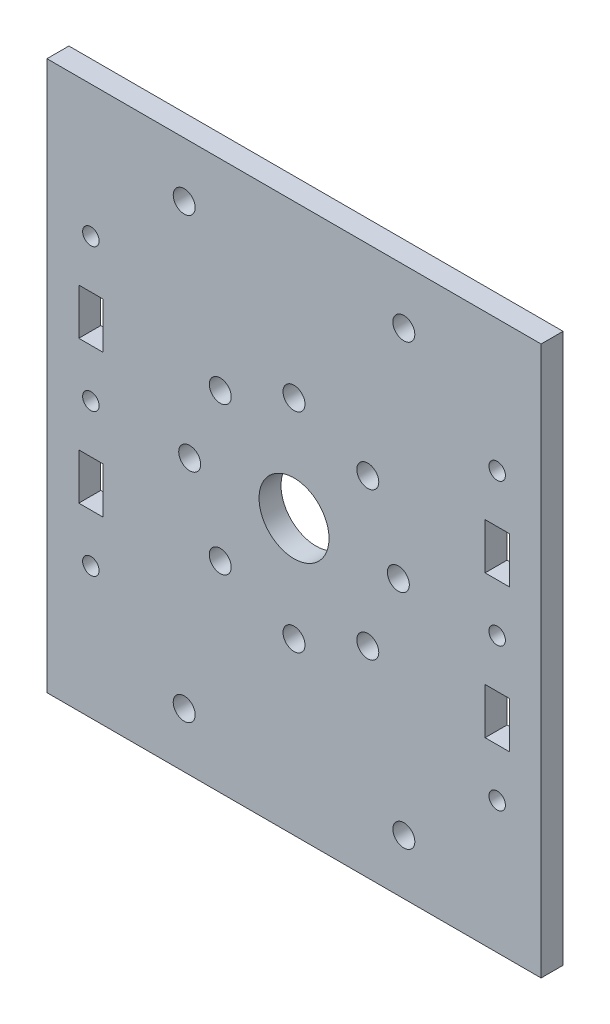
SolidWorks part; units mm, degrees
ref_plane "前视基准面" through (0, 0, 0) normal (0, 0, 1) x (1, 0, 0)
ref_plane "上视基准面" through (0, 0, 0) normal (0, 1, 0) x (1, 0, 0)
ref_plane "右视基准面" through (0, 0, 0) normal (1, 0, 0) x (0, 0, -1)
sketch "草图1" plane through (0, 0, 0) normal (0, 0, 1) x (1, 0, 0)
  line L0 (0, 0) -> (0, -40) construction
  line L1 (0, -40) -> (20, -40) construction
  line L2 (0, -40) -> (-20, -40) construction
  line L3 (0, 0) -> (19, 0) construction
  line L4 (34.8, -17.2) -> (39.2, -17.2)
  line L5 (45, -50) -> (-45, -50)
  line L6 (45, -50) -> (45, 50)
  line L7 (45, 50) -> (-45, 50)
  line L8 (-45, -50) -> (-45, 50)
  line L9 (45, -50) -> (-45, 50) construction
  line L10 (45, 50) -> (-45, -50) construction
  line L11 (34.8, 17.2) -> (39.2, 17.2)
  line L12 (34.8, 17.2) -> (34.8, 8.8)
  line L13 (34.8, 8.8) -> (39.2, 8.8)
  line L14 (39.2, 17.2) -> (39.2, 8.8)
  line L15 (34.8, 17.2) -> (39.2, 8.8) construction
  line L16 (34.8, 8.8) -> (39.2, 17.2) construction
  line L17 (34.8, -17.2) -> (34.8, -8.8)
  line L18 (39.2, -17.2) -> (39.2, -8.8)
  line L19 (34.8, -8.8) -> (39.2, -8.8)
  line L20 (0, 19) -> (0, 0) construction
  line L21 (-34.8, 17.2) -> (-39.2, 17.2)
  line L22 (-39.2, 17.2) -> (-39.2, 8.8)
  line L23 (-34.8, 17.2) -> (-34.8, 8.8)
  line L24 (-34.8, 8.8) -> (-39.2, 8.8)
  line L25 (-34.8, -8.8) -> (-39.2, -8.8)
  line L26 (-34.8, -17.2) -> (-39.2, -17.2)
  line L27 (-34.8, -17.2) -> (-34.8, -8.8)
  line L28 (-39.2, -17.2) -> (-39.2, -8.8)
  circle A0 centre (0, 0) radius 19 construction
  circle A1 centre (0, 0) radius 6.3725
  circle A2 centre (0, -19) radius 2
  circle A3 centre (-13.435, -13.435) radius 2
  circle A4 centre (-19, 0) radius 2
  circle A5 centre (-13.435, 13.435) radius 2
  circle A6 centre (0, 19) radius 2
  circle A7 centre (13.435, 13.435) radius 2
  circle A8 centre (19, 0) radius 2
  circle A9 centre (13.435, -13.435) radius 2
  circle A10 centre (-20, -40) radius 2
  circle A11 centre (20, -40) radius 2
  circle A12 centre (20, 40) radius 2
  circle A13 centre (-20, 40) radius 2
  circle A14 centre (37, 0) radius 1.5
  circle A15 centre (37, 26) radius 1.5
  circle A16 centre (37, -26) radius 1.5
  circle A17 centre (-37, 0) radius 1.5
  circle A18 centre (-37, -26) radius 1.5
  circle A19 centre (-37, 26) radius 1.5
  point P36 (37, 13)
  dimension "D1" = 4
  dimension "D2" = 38
  dimension "D4" = 90
  dimension "D5" = 37
  dimension "D7" = 13
  dimension "D3" = 40
  dimension "D6" = 13
  dimension "D8" = 100
extrude "凸台-拉伸1" add sketch "草图1" along normal blind 4
